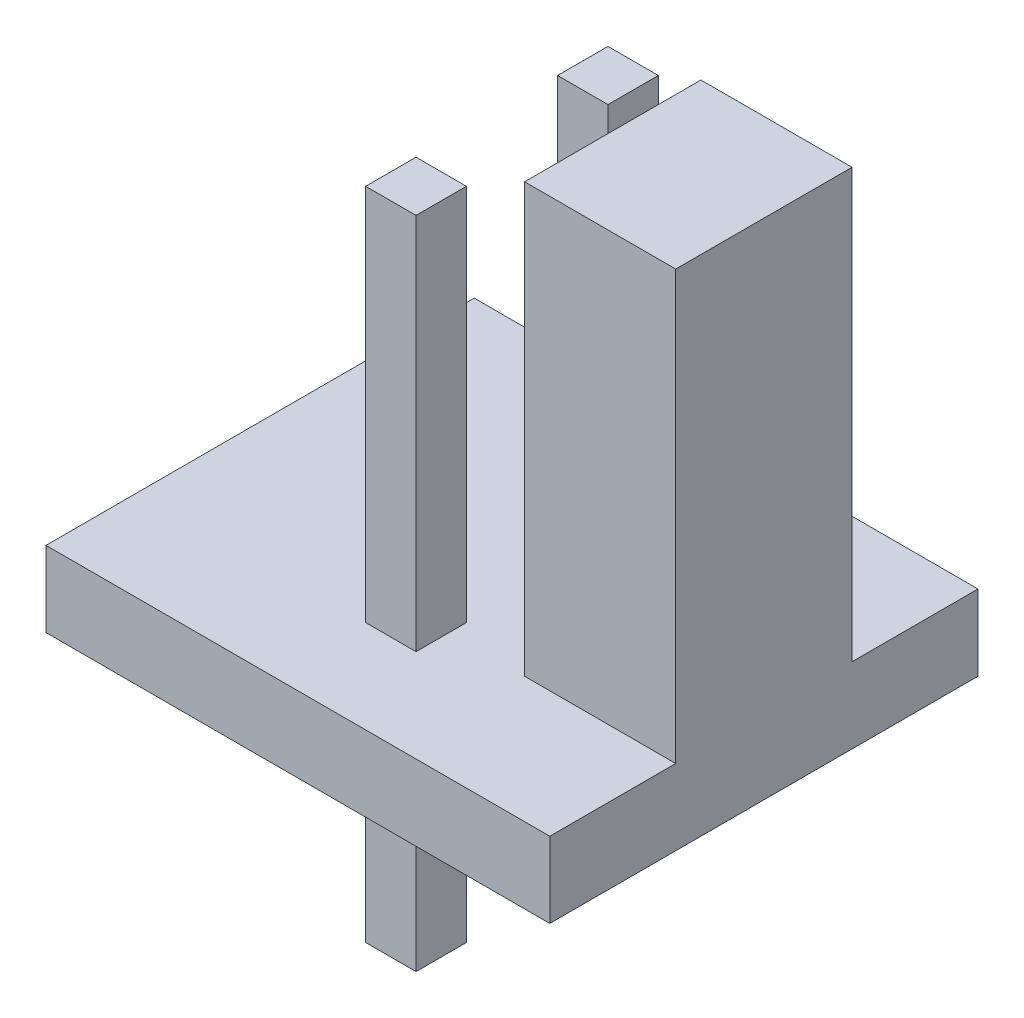
SolidWorks part; units mm, degrees
ref_plane "前视基准面" through (0, 0, 0) normal (0, 0, 1) x (1, 0, 0)
ref_plane "上视基准面" through (0, 0, 0) normal (0, 1, 0) x (1, 0, 0)
ref_plane "右视基准面" through (0, 0, 0) normal (1, 0, 0) x (0, 0, -1)
sketch "草图1" plane through (0, 0, 0) normal (0, 1, 0) x (1, 0, 0)
  line L0 (0, 11.3571) -> (0, -8.6742) construction
  line L1 (-5, 4.25) -> (5, 4.25)
  line L2 (-5, 4.25) -> (-5, -4.25)
  line L3 (-5, -4.25) -> (5, -4.25)
  line L4 (5, 4.25) -> (5, -4.25)
  line L5 (-11.8577, 0) -> (16.1453, 0) construction
  dimension "D1" = 10
  dimension "D2" = 8.5
extrude "拉伸1" add sketch "草图1" along normal blind 10
sketch "草图2" plane through (0, 10, 0) normal (0, 1, 0) x (-1, 0, 0)
  line L0 (-5, 1.75) -> (-5, 4.25)
  line L1 (-5, 4.25) -> (-5, -4.25) construction
  line L2 (-5, 4.25) -> (5, 4.25)
  line L5 (5, 4.25) -> (5, -4.25)
  line L6 (5, -4.25) -> (-5, -4.25)
  line L7 (-5, -4.25) -> (5, -4.25) construction
  line L8 (-5, -4.25) -> (-5, -1.75)
  line L10 (-5, -1.75) -> (-2, -1.75)
  line L11 (-2, -1.75) -> (-2, 1.75)
  line L12 (-2, 1.75) -> (-5, 1.75)
  line L13 (-6.554, 0) -> (7.9913, 0) construction
  dimension "D1" = 3.5
  dimension "D2" = 3
extrude "切除-拉伸1" cut sketch "草图2" against normal offset from surface (8.5 mm away) 1.5 up to face at (0, 0, 0)
sketch "草图3" plane through (0, 0, 0) normal (0, -1, 0) x (1, 0, 0)
  line L0 (4.5117, 0) -> (-4.6667, 0) construction
  line L1 (3.6187, 1.905) -> (-1.0308, 1.905) construction
  line L2 (0.5, 2.405) -> (-0.5, 2.405)
  line L3 (0.5, 2.405) -> (0.5, 1.405)
  line L4 (0.5, 1.405) -> (-0.5, 1.405)
  line L5 (-0.5, 2.405) -> (-0.5, 1.405)
  line L6 (0, 3.5474) -> (0, 0.8266) construction
  line L7 (-5, -4.25) -> (-5, 4.25) construction
  line L8 (-0.5, -2.405) -> (-0.5, -1.405)
  line L9 (0.5, -1.405) -> (-0.5, -1.405)
  line L10 (0.5, -2.405) -> (0.5, -1.405)
  line L11 (0.5, -2.405) -> (-0.5, -2.405)
  dimension "D1" = 1
  dimension "D2" = 1
  dimension "D3" = 1.905
  dimension "D4" = 5
extrude "拉伸2" add sketch "草图3" along normal blind 4 and the other way offset from surface (9 mm away) 1 other way up to face at (3.5, 10, 0)
